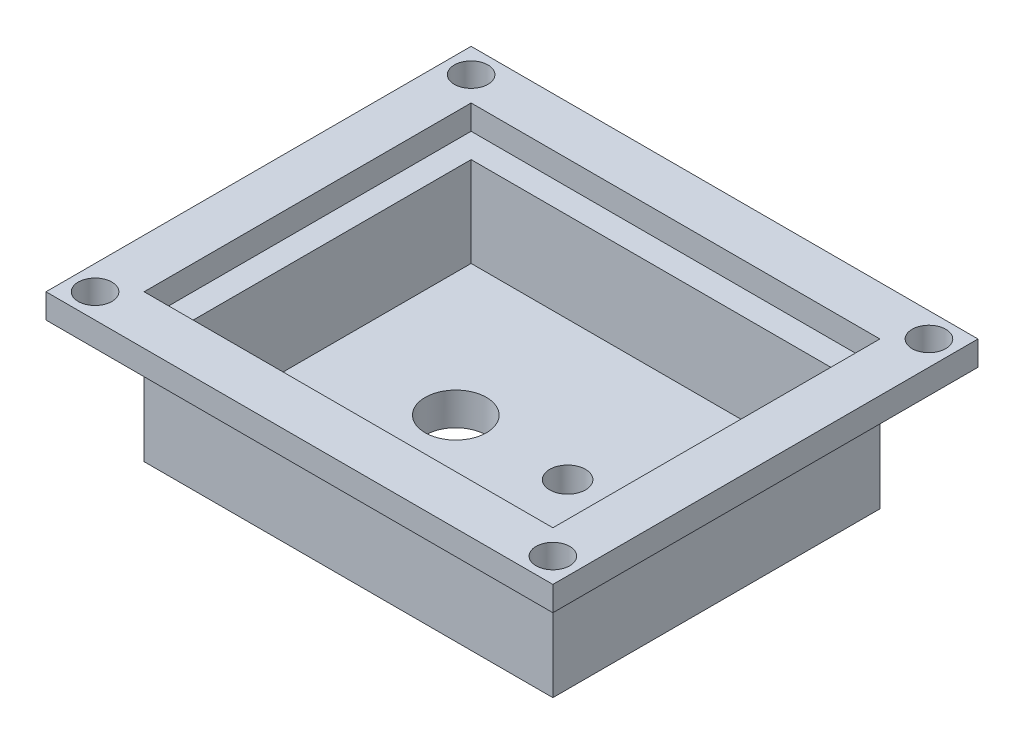
SolidWorks part; units mm, degrees
ref_plane "Front Plane" through (0, 0, 0) normal (0, 0, 1) x (1, 0, 0)
ref_plane "Top Plane" through (0, 0, 0) normal (0, 1, 0) x (1, 0, 0)
ref_plane "Right Plane" through (0, 0, 0) normal (1, 0, 0) x (0, 0, -1)
sketch "Sketch1" plane through (0, 0, 0) normal (0, 1, 0) x (1, 0, 0)
  line L1 (-31.75, -25.4) -> (31.75, -25.4)
  line L2 (-31.75, -25.4) -> (-31.75, 25.4)
  line L3 (-31.75, 25.4) -> (31.75, 25.4)
  line L4 (31.75, -25.4) -> (31.75, 25.4)
  line L5 (-31.75, -25.4) -> (31.75, 25.4) construction
  line L6 (-31.75, 25.4) -> (31.75, -25.4) construction
  point P0 (0, 0)
  dimension "D1" = 63.5
  dimension "D2" = 50.8
extrude "Boss-Extrude1" add sketch "Sketch1" along normal blind 19.05
sketch "Sketch2" plane through (0, 19.05, 0) normal (0, 1, 0) x (1, 0, 0)
  line L1 (-27.94, -21.59) -> (27.94, -21.59)
  line L2 (-27.94, -21.59) -> (-27.94, 21.59)
  line L3 (-27.94, 21.59) -> (27.94, 21.59)
  line L4 (27.94, -21.59) -> (27.94, 21.59)
  line L5 (-27.94, -21.59) -> (27.94, 21.59) construction
  line L6 (-27.94, 21.59) -> (27.94, -21.59) construction
  point P0 (0, 0)
  dimension "D1" = 55.88
  dimension "D2" = 43.18
extrude "Cut-Extrude1" cut sketch "Sketch2" against normal blind 13.97
sketch "Sketch3" plane through (0, 5.08, 0) normal (0, 1, 0) x (1, 0, 0)
  circle A0 centre (-8.7312, 0) radius 4.7625
  circle A1 centre (8.636, 0) radius 2.7781
  dimension "D1" = 9.525
  dimension "D3" = 5.5562
  dimension "D2" = 8.7312
  dimension "D4" = 8.636
extrude "Cut-Extrude2" cut sketch "Sketch3" against normal blind 13.97
sketch "Sketch19" plane through (0, 19.05, 0) normal (0, 1, 0) x (1, 0, 0)
  line L0 (39.37, -33.02) -> (39.37, 33.02)
  line L1 (39.37, 33.02) -> (-39.37, 33.02)
  line L2 (-39.37, 33.02) -> (-39.37, -33.02)
  line L3 (-39.37, -33.02) -> (39.37, -33.02)
  line L4 (31.75, -25.4) -> (31.75, 25.4)
  line L5 (31.75, 25.4) -> (-31.75, 25.4)
  line L6 (-31.75, 25.4) -> (-31.75, -25.4)
  line L7 (-31.75, -25.4) -> (31.75, -25.4)
  line L8 (31.75, -25.4) -> (31.75, 25.4)
  line L9 (31.75, 25.4) -> (-31.75, 25.4)
  line L10 (-31.75, 25.4) -> (-31.75, -25.4)
  line L11 (-31.75, -25.4) -> (31.75, -25.4)
  line M9 (31.75, -25.4) -> (31.75, 25.4)
  line M10 (31.75, 25.4) -> (-31.75, 25.4)
  line M11 (-31.75, 25.4) -> (-31.75, -25.4)
  line M12 (-31.75, -25.4) -> (31.75, -25.4)
  dimension "D1" = 0
  dimension "D2" = 7.62
extrude "Boss-Extrude5" add sketch "Sketch19" along normal blind 3.81 separate body contours L2 L3 L0 L1 M9 M12 M11 M10
hole_wizard "#10 Clearance Hole1" positions "Sketch22" profile "Sketch21" hole size "#10" standard "ANSI Inch"
sketch "Sketch22" plane through (0, 22.86, 0) normal (0, 1, 0) x (1, 0, 0)
  line L0 (-39.37, 33.02) -> (-39.37, -33.02) construction
  line L1 (39.37, 33.02) -> (-39.37, 33.02) construction
  line L2 (39.37, -33.02) -> (39.37, 33.02) construction
  line L3 (-39.37, -33.02) -> (39.37, -33.02) construction
  point P1 (35.56, 29.21)
  point P3 (35.56, -29.21)
  point P5 (-35.56, -29.21)
  point P7 (-35.56, 29.21)
  point P23 (-35.56, 29.21)
  point P25 (35.56, 29.21)
  point P27 (35.56, -29.21)
  point P29 (-35.56, -29.21)
  dimension "D1" = 3.81
  dimension "D2" = 3.81
  dimension "D3" = 3.81
  dimension "D4" = 3.81
  dimension "D5" = 3.81
  dimension "D6" = 3.81
  dimension "D7" = 3.81
  dimension "D8" = 3.81
sketch "Sketch21" plane through (35.56, 22.86, -29.21) normal (1, 0, 0) x (0, 0, 1)
  line L0 (0, 0) -> (0, 24.432)
  line L1 (0, 24.432) -> (2.6162, 22.86)
  line L2 (2.6162, 22.86) -> (2.6162, 0)
  line L5 (2.6162, 0) -> (0, 0)
  line L10 (0, 24.432) -> (-2.6162, 22.86) construction
  line L11 (0, -6.35) -> (0, 107.95) construction
  dimension "Hole Dia." = 5.2324
  dimension "Hole Depth" = 22.86
  dimension "Drill Angle" = 118
